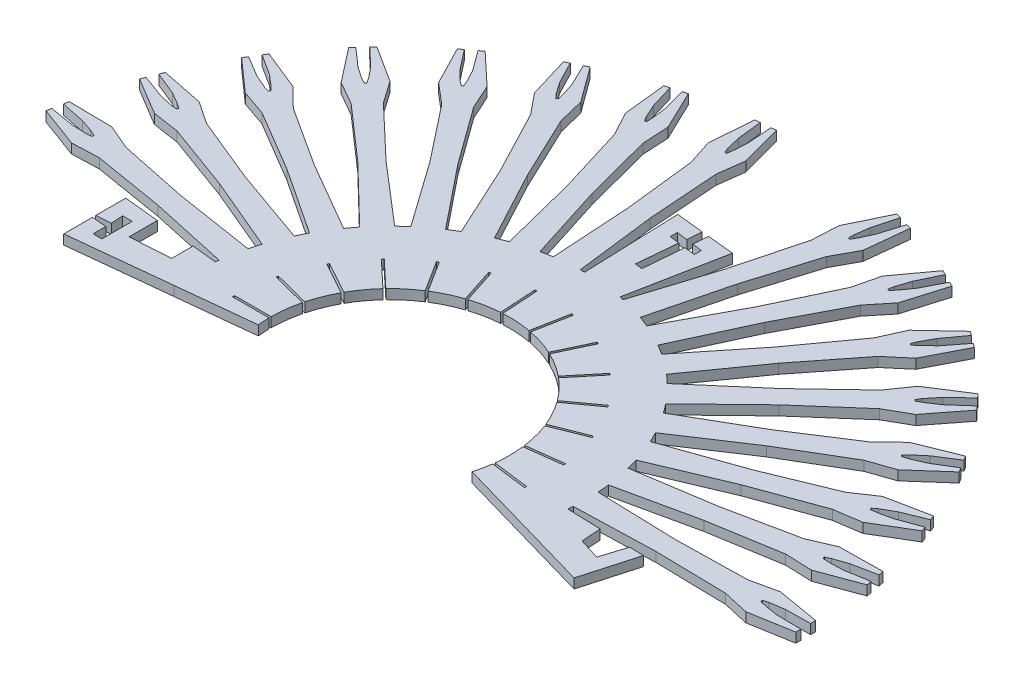
SolidWorks part; units mm, degrees
ref_plane "Front Plane" through (0, 0, 0) normal (0, 0, 1) x (1, 0, 0)
ref_plane "Top Plane" through (0, 0, 0) normal (0, 1, 0) x (1, 0, 0)
ref_plane "Right Plane" through (0, 0, 0) normal (1, 0, 0) x (0, 0, -1)
sketch "Sketch1" plane through (0, 0, 0) normal (0, 1, 0) x (1, 0, 0)
  line L5558 (72.849, 49.9) -> (72.743, 47.748) construction
  line L5559 (72.743, 47.748) -> (72.425, 45.667) construction
  line L5560 (72.425, 45.667) -> (71.896, 43.656) construction
  line L5561 (71.896, 43.656) -> (71.208, 41.716) construction
  line L5562 (71.208, 41.716) -> (70.309, 39.899) construction
  line L5563 (70.309, 39.899) -> (69.286, 38.171) construction
  line L5564 (69.286, 38.171) -> (66.71, 35.048) construction
  line L5565 (66.71, 35.048) -> (63.588, 32.491) construction
  line L5566 (63.588, 32.491) -> (61.877, 31.45) construction
  line L5567 (61.877, 31.45) -> (60.043, 30.551) construction
  line L5568 (60.043, 30.551) -> (58.12, 29.863) construction
  line L5569 (58.12, 29.863) -> (56.109, 29.333) construction
  line L5570 (56.109, 29.333) -> (54.01, 29.016) construction
  line L5571 (54.01, 29.016) -> (51.876, 28.91) construction
  line L5572 (51.876, 28.91) -> (49.724, 29.016) construction
  line L5573 (49.724, 29.016) -> (47.643, 29.333) construction
  line L5574 (47.643, 29.333) -> (45.632, 29.863) construction
  line L5575 (45.632, 29.863) -> (43.692, 30.551) construction
  line L5576 (43.692, 30.551) -> (41.839, 31.45) construction
  line L5577 (41.839, 31.45) -> (40.128, 32.491) construction
  line L5578 (40.128, 32.491) -> (37.006, 35.048) construction
  line L5579 (37.006, 35.048) -> (34.431, 38.171) construction
  line L5580 (34.431, 38.171) -> (33.408, 39.899) construction
  line L5581 (33.408, 39.899) -> (32.508, 41.716) construction
  line L5582 (32.508, 41.716) -> (31.821, 43.656) construction
  line L5583 (31.821, 43.656) -> (31.291, 45.667) construction
  line L5584 (31.291, 45.667) -> (30.974, 47.748) construction
  line L5585 (30.974, 47.748) -> (30.868, 49.9) construction
  line L5586 (30.868, 49.9) -> (30.974, 52.035) construction
  line L5587 (30.974, 52.035) -> (31.291, 54.134) construction
  line L5588 (31.291, 54.134) -> (31.821, 56.145) construction
  line L5589 (31.821, 56.145) -> (32.508, 58.067) construction
  line L5590 (32.508, 58.067) -> (33.408, 59.919) construction
  line L5591 (33.408, 59.919) -> (34.431, 61.648) construction
  line L5592 (34.431, 61.648) -> (37.006, 64.77) construction
  line L5593 (37.006, 64.77) -> (40.128, 67.328) construction
  line L5594 (40.128, 67.328) -> (41.839, 68.368) construction
  line L5595 (41.839, 68.368) -> (43.692, 69.268) construction
  line L5596 (43.692, 69.268) -> (45.632, 69.956) construction
  line L5597 (45.632, 69.956) -> (47.643, 70.485) construction
  line L5598 (47.643, 70.485) -> (49.724, 70.803) construction
  line L5599 (49.724, 70.803) -> (51.876, 70.908) construction
  line L5600 (51.876, 70.908) -> (54.01, 70.803) construction
  line L5601 (54.01, 70.803) -> (56.109, 70.485) construction
  line L5602 (56.109, 70.485) -> (58.12, 69.956) construction
  line L5603 (58.12, 69.956) -> (60.043, 69.268) construction
  line L5604 (60.043, 69.268) -> (61.877, 68.368) construction
  line L5605 (61.877, 68.368) -> (63.588, 67.328) construction
  line L5606 (63.588, 67.328) -> (66.71, 64.77) construction
  line L5607 (66.71, 64.77) -> (69.286, 61.648) construction
  line L5608 (69.286, 61.648) -> (70.309, 59.919) construction
  line L5609 (70.309, 59.919) -> (71.208, 58.067) construction
  line L5610 (71.208, 58.067) -> (71.896, 56.145) construction
  line L5611 (71.896, 56.145) -> (72.425, 54.134) construction
  line L5612 (72.425, 54.134) -> (72.743, 52.035) construction
  line L5613 (72.743, 52.035) -> (72.849, 49.9) construction
  line L5614 (62.054, 49.9) -> (61.842, 47.854) construction
  line L5615 (61.842, 47.854) -> (61.26, 45.932) construction
  line L5616 (61.26, 45.932) -> (60.307, 44.203) construction
  line L5617 (60.307, 44.203) -> (59.055, 42.704) construction
  line L5618 (59.055, 42.704) -> (57.556, 41.451) construction
  line L5619 (57.556, 41.451) -> (55.827, 40.499) construction
  line L5620 (55.827, 40.499) -> (53.922, 39.917) construction
  line L5621 (53.922, 39.917) -> (51.858, 39.705) construction
  line L5622 (51.858, 39.705) -> (49.795, 39.917) construction
  line L5623 (49.795, 39.917) -> (47.89, 40.499) construction
  line L5624 (47.89, 40.499) -> (46.143, 41.451) construction
  line L5625 (46.143, 41.451) -> (44.644, 42.704) construction
  line L5626 (44.644, 42.704) -> (43.392, 44.203) construction
  line L5627 (43.392, 44.203) -> (42.439, 45.932) construction
  line L5628 (42.439, 45.932) -> (41.857, 47.854) construction
  line L5629 (41.857, 47.854) -> (41.645, 49.9) construction
  line L5630 (41.645, 49.9) -> (41.857, 51.964) construction
  line L5631 (41.857, 51.964) -> (42.439, 53.869) construction
  line L5632 (42.439, 53.869) -> (43.392, 55.615) construction
  line L5633 (43.392, 55.615) -> (44.644, 57.115) construction
  line L5634 (44.644, 57.115) -> (46.143, 58.367) construction
  line L5635 (46.143, 58.367) -> (47.89, 59.32) construction
  line L5636 (47.89, 59.32) -> (49.795, 59.902) construction
  line L5637 (49.795, 59.902) -> (51.858, 60.113) construction
  line L5638 (51.858, 60.113) -> (53.922, 59.902) construction
  line L5639 (53.922, 59.902) -> (55.827, 59.32) construction
  line L5640 (55.827, 59.32) -> (57.556, 58.367) construction
  line L5641 (57.556, 58.367) -> (59.055, 57.115) construction
  line L5642 (59.055, 57.115) -> (60.307, 55.615) construction
  line L5643 (60.307, 55.615) -> (61.26, 53.869) construction
  line L5644 (61.26, 53.869) -> (61.842, 51.964) construction
  line L5645 (61.842, 51.964) -> (62.054, 49.9) construction
  line L5646 (30.85, 49.9) -> (51.841, 49.9) construction
  line L5647 (53.675, 70.82) -> (51.841, 49.9) construction
  line L5648 (72.531, 46.249) -> (51.858, 49.9) construction
  line L5649 (72.796, 48.436) -> (51.841, 49.9) construction
  line L5650 (51.488, 70.891) -> (51.841, 49.9) construction
  line L5651 (55.862, 70.52) -> (51.858, 49.9) construction
  line L5652 (30.956, 47.696) -> (51.841, 49.9) construction
  line L5653 (30.956, 52.088) -> (51.841, 49.9) construction
  line L5654 (72.037, 44.115) -> (51.841, 49.9) construction
  line L5655 (62.406, 49.177) -> (67.045, 49.424) construction
  line L5656 (67.345, 50.077) -> (67.469, 50.324) construction
  line L5657 (67.469, 50.324) -> (67.68, 50.377) construction
  line L5658 (67.68, 50.377) -> (67.892, 50.271) construction
  line L5659 (67.892, 50.271) -> (67.945, 50.059) construction
  line L5660 (67.945, 50.059) -> (67.839, 49.848) construction
  line L5661 (67.839, 49.848) -> (67.628, 49.759) construction
  line L5662 (67.628, 49.759) -> (67.416, 49.865) construction
  line L5663 (67.416, 49.865) -> (67.345, 50.077) construction
  line L5664 (69.832, 50.094) -> (69.938, 50.341) construction
  line L5665 (69.938, 50.341) -> (70.168, 50.394) construction
  line L5666 (70.168, 50.394) -> (70.379, 50.288) construction
  line L5667 (70.379, 50.288) -> (70.432, 50.077) construction
  line L5668 (70.432, 50.077) -> (70.326, 49.865) construction
  line L5669 (70.326, 49.865) -> (70.115, 49.777) construction
  line L5670 (70.115, 49.777) -> (69.903, 49.883) construction
  line L5671 (69.903, 49.883) -> (69.832, 50.094) construction
  line L5672 (67.045, 49.424) -> (71.702, 49.477) construction
  line L5673 (71.914, 50.094) -> (71.702, 49.477) construction
  line L5674 (62.389, 50.835) -> (67.045, 50.659) construction
  line L5675 (67.045, 50.659) -> (71.702, 50.712) construction
  line L5676 (71.914, 50.094) -> (71.702, 50.712) construction
  line L5677 (70.132, 50.377) -> (67.645, 50.359) construction
  line L5678 (70.15, 49.777) -> (67.645, 49.742) construction
  line L5679 (57.344, 49.953) -> (51.841, 49.9) construction
  line L5680 (62.353, 51.118) -> (66.887, 52.229) construction
  line L5681 (67.045, 52.917) -> (67.345, 53.252) construction
  line L5682 (67.345, 53.252) -> (67.557, 53.199) construction
  line L5683 (67.557, 53.199) -> (67.663, 52.987) construction
  line L5684 (67.663, 52.987) -> (67.61, 52.776) construction
  line L5685 (67.61, 52.776) -> (67.398, 52.652) construction
  line L5686 (67.398, 52.652) -> (67.187, 52.723) construction
  line L5687 (67.187, 52.723) -> (67.045, 52.917) construction
  line L5688 (69.48, 53.393) -> (69.779, 53.746) construction
  line L5689 (69.779, 53.746) -> (69.991, 53.693) construction
  line L5690 (69.991, 53.693) -> (70.097, 53.481) construction
  line L5691 (70.097, 53.481) -> (70.044, 53.269) construction
  line L5692 (70.044, 53.269) -> (69.832, 53.128) construction
  line L5693 (69.832, 53.128) -> (69.621, 53.217) construction
  line L5694 (69.621, 53.217) -> (69.48, 53.393) construction
  line L5695 (66.887, 52.229) -> (71.455, 53.128) construction
  line L5696 (71.543, 53.763) -> (71.455, 53.128) construction
  line L5697 (62.036, 52.758) -> (66.64, 53.428) construction
  line L5698 (66.64, 53.428) -> (71.208, 54.328) construction
  line L5699 (71.543, 53.781) -> (71.208, 54.328) construction
  line L5700 (69.744, 53.728) -> (67.292, 53.252) construction
  line L5701 (69.85, 53.128) -> (67.416, 52.634) construction
  line L5702 (57.238, 50.959) -> (51.841, 49.9) construction
  line L5703 (61.965, 53.023) -> (66.199, 54.945) construction
  line L5704 (66.234, 55.651) -> (66.446, 56.039) construction
  line L5705 (66.446, 56.039) -> (66.693, 56.021) construction
  line L5706 (66.693, 56.021) -> (66.851, 55.827) construction
  line L5707 (66.851, 55.827) -> (66.64, 55.457) construction
  line L5708 (66.64, 55.457) -> (66.393, 55.492) construction
  line L5709 (66.393, 55.492) -> (66.234, 55.651) construction
  line L5710 (68.545, 56.568) -> (68.756, 56.956) construction
  line L5711 (68.756, 56.956) -> (69.003, 56.938) construction
  line L5712 (69.003, 56.938) -> (69.162, 56.744) construction
  line L5713 (69.162, 56.744) -> (68.95, 56.374) construction
  line L5714 (68.95, 56.374) -> (68.703, 56.409) construction
  line L5715 (68.703, 56.409) -> (68.545, 56.568) construction
  line L5716 (66.199, 54.945) -> (70.52, 56.656) construction
  line L5717 (70.503, 57.309) -> (70.52, 56.656) construction
  line L5718 (61.348, 54.575) -> (65.74, 56.092) construction
  line L5719 (65.74, 56.092) -> (70.079, 57.803) construction
  line L5720 (70.503, 57.309) -> (70.079, 57.803) construction
  line L5721 (68.739, 56.938) -> (66.41, 56.021) construction
  line L5722 (68.968, 56.374) -> (66.64, 55.439) construction
  line L5723 (56.956, 51.929) -> (51.841, 49.9) construction
  line L5724 (61.225, 54.822) -> (65.035, 57.485) construction
  line L5725 (64.946, 58.191) -> (65.07, 58.614) construction
  line L5726 (65.07, 58.614) -> (65.317, 58.632) construction
  line L5727 (65.317, 58.632) -> (65.493, 58.473) construction
  line L5728 (65.493, 58.473) -> (65.528, 58.244) construction
  line L5729 (65.528, 58.244) -> (65.37, 58.05) construction
  line L5730 (65.37, 58.05) -> (64.946, 58.191) construction
  line L5731 (67.045, 59.514) -> (67.169, 59.937) construction
  line L5732 (67.169, 59.937) -> (67.416, 59.955) construction
  line L5733 (67.416, 59.955) -> (67.592, 59.796) construction
  line L5734 (67.592, 59.796) -> (67.628, 59.567) construction
  line L5735 (67.628, 59.567) -> (67.469, 59.373) construction
  line L5736 (67.469, 59.373) -> (67.045, 59.514) construction
  line L5737 (65.035, 57.485) -> (68.968, 59.972) construction
  line L5738 (68.827, 60.607) -> (68.968, 59.972) construction
  line L5739 (60.325, 56.233) -> (64.382, 58.526) construction
  line L5740 (64.382, 58.526) -> (68.315, 61.013) construction
  line L5741 (68.827, 60.607) -> (68.315, 61.013) construction
  line L5742 (67.169, 59.919) -> (65.052, 58.579) construction
  line L5743 (67.486, 59.39) -> (65.37, 58.067) construction
  line L5744 (56.497, 52.828) -> (51.858, 49.9) construction
  line L5745 (60.149, 56.444) -> (63.429, 59.761) construction
  line L5746 (63.2, 60.448) -> (63.147, 60.678) construction
  line L5747 (63.147, 60.678) -> (63.288, 60.889) construction
  line L5748 (63.288, 60.889) -> (63.5, 60.942) construction
  line L5749 (63.5, 60.942) -> (63.712, 60.837) construction
  line L5750 (63.712, 60.837) -> (63.765, 60.607) construction
  line L5751 (63.765, 60.607) -> (63.659, 60.396) construction
  line L5752 (63.659, 60.396) -> (63.412, 60.343) construction
  line L5753 (63.412, 60.343) -> (63.2, 60.448) construction
  line L5754 (65.017, 62.124) -> (64.964, 62.371) construction
  line L5755 (64.964, 62.371) -> (65.105, 62.583) construction
  line L5756 (65.105, 62.583) -> (65.317, 62.636) construction
  line L5757 (65.317, 62.636) -> (65.528, 62.53) construction
  line L5758 (65.528, 62.53) -> (65.581, 62.283) construction
  line L5759 (65.581, 62.283) -> (65.476, 62.071) construction
  line L5760 (65.476, 62.071) -> (65.229, 62.018) construction
  line L5761 (65.229, 62.018) -> (65.017, 62.124) construction
  line L5762 (63.429, 59.761) -> (66.834, 62.936) construction
  line L5763 (66.587, 63.535) -> (66.834, 62.936) construction
  line L5764 (59.02, 57.679) -> (62.583, 60.678) construction
  line L5765 (62.583, 60.678) -> (66.005, 63.835) construction
  line L5766 (66.587, 63.535) -> (66.005, 63.835) construction
  line L5767 (65.07, 62.548) -> (63.235, 60.854) construction
  line L5768 (65.493, 62.089) -> (63.659, 60.396) construction
  line L5769 (55.88, 53.622) -> (51.841, 49.9) construction
  line L5770 (58.808, 57.873) -> (61.419, 61.718) construction
  line L5771 (61.083, 62.353) -> (60.995, 62.583) construction
  line L5772 (60.995, 62.583) -> (61.083, 62.794) construction
  line L5773 (61.083, 62.794) -> (61.295, 62.9) construction
  line L5774 (61.295, 62.9) -> (61.507, 62.83) construction
  line L5775 (61.507, 62.83) -> (61.613, 62.618) construction
  line L5776 (61.613, 62.618) -> (61.524, 62.371) construction
  line L5777 (61.524, 62.371) -> (61.313, 62.301) construction
  line L5778 (61.313, 62.301) -> (61.083, 62.353) construction
  line L5779 (62.565, 64.329) -> (62.477, 64.576) construction
  line L5780 (62.477, 64.576) -> (62.565, 64.788) construction
  line L5781 (62.565, 64.788) -> (62.777, 64.893) construction
  line L5782 (62.777, 64.893) -> (62.988, 64.805) construction
  line L5783 (62.988, 64.805) -> (63.094, 64.594) construction
  line L5784 (63.094, 64.594) -> (63.006, 64.364) construction
  line L5785 (63.006, 64.364) -> (62.794, 64.276) construction
  line L5786 (62.794, 64.276) -> (62.565, 64.329) construction
  line L5787 (61.419, 61.718) -> (64.206, 65.458) construction
  line L5788 (63.835, 66.005) -> (64.206, 65.458) construction
  line L5789 (57.485, 58.861) -> (60.431, 62.459) construction
  line L5790 (60.431, 62.459) -> (63.2, 66.199) construction
  line L5791 (63.835, 66.005) -> (63.2, 66.199) construction
  line L5792 (62.53, 64.752) -> (61.031, 62.759) construction
  line L5793 (63.024, 64.382) -> (61.524, 62.389) construction
  line L5794 (55.122, 54.31) -> (51.858, 49.9) construction
  line L5795 (57.238, 59.002) -> (59.09, 63.271) construction
  line L5796 (58.649, 63.835) -> (58.508, 64.047) construction
  line L5797 (58.508, 64.047) -> (58.561, 64.258) construction
  line L5798 (58.561, 64.258) -> (58.755, 64.417) construction
  line L5799 (58.755, 64.417) -> (58.967, 64.364) construction
  line L5800 (58.967, 64.364) -> (59.126, 64.17) construction
  line L5801 (59.126, 64.17) -> (59.073, 63.941) construction
  line L5802 (59.073, 63.941) -> (58.879, 63.8) construction
  line L5803 (58.879, 63.8) -> (58.649, 63.835) construction
  line L5804 (59.743, 66.058) -> (59.602, 66.269) construction
  line L5805 (59.602, 66.269) -> (59.655, 66.481) construction
  line L5806 (59.655, 66.481) -> (59.849, 66.604) construction
  line L5807 (59.849, 66.604) -> (60.06, 66.587) construction
  line L5808 (60.06, 66.587) -> (60.219, 66.393) construction
  line L5809 (60.219, 66.393) -> (60.166, 66.163) construction
  line L5810 (60.166, 66.163) -> (59.972, 66.022) construction
  line L5811 (59.972, 66.022) -> (59.743, 66.058) construction
  line L5812 (59.09, 63.271) -> (61.136, 67.451) construction
  line L5813 (60.695, 67.927) -> (61.136, 67.451) construction
  line L5814 (55.739, 59.743) -> (57.979, 63.818) construction
  line L5815 (57.979, 63.818) -> (60.025, 67.998) construction
  line L5816 (60.678, 67.927) -> (60.025, 67.998) construction
  line L5817 (59.619, 66.463) -> (58.526, 64.223) construction
  line L5818 (60.184, 66.181) -> (59.073, 63.941) construction
  line L5819 (54.257, 54.822) -> (51.841, 49.9) construction
  line L5820 (55.457, 59.849) -> (56.497, 64.382) construction
  line L5821 (55.951, 64.841) -> (55.792, 64.999) construction
  line L5822 (55.792, 64.999) -> (55.792, 65.246) construction
  line L5823 (55.792, 65.246) -> (55.951, 65.423) construction
  line L5824 (55.951, 65.423) -> (56.18, 65.423) construction
  line L5825 (56.18, 65.423) -> (56.339, 65.264) construction
  line L5826 (56.339, 65.264) -> (56.339, 65.035) construction
  line L5827 (56.339, 65.035) -> (56.18, 64.876) construction
  line L5828 (56.18, 64.876) -> (55.951, 64.841) construction
  line L5829 (56.603, 67.239) -> (56.444, 67.398) construction
  line L5830 (56.444, 67.398) -> (56.444, 67.628) construction
  line L5831 (56.444, 67.628) -> (56.603, 67.822) construction
  line L5832 (56.603, 67.822) -> (56.85, 67.822) construction
  line L5833 (56.85, 67.822) -> (57.009, 67.663) construction
  line L5834 (57.009, 67.663) -> (57.009, 67.416) construction
  line L5835 (57.009, 67.416) -> (56.85, 67.257) construction
  line L5836 (56.85, 67.257) -> (56.603, 67.239) construction
  line L5837 (56.497, 64.382) -> (57.732, 68.88) construction
  line L5838 (57.203, 69.25) -> (57.732, 68.88) construction
  line L5839 (53.852, 60.29) -> (55.298, 64.717) construction
  line L5840 (55.298, 64.717) -> (56.533, 69.197) construction
  line L5841 (57.185, 69.25) -> (56.533, 69.197) construction
  line L5842 (56.427, 67.61) -> (55.757, 65.211) construction
  line L5843 (57.009, 67.451) -> (56.356, 65.035) construction
  line L5844 (53.305, 55.192) -> (51.841, 49.9) construction
  line L5845 (51.664, 60.484) -> (50.994, 65.088) construction
  line L5846 (50.324, 65.317) -> (50.112, 65.423) construction
  line L5847 (50.112, 65.423) -> (50.024, 65.634) construction
  line L5848 (50.024, 65.634) -> (50.112, 65.846) construction
  line L5849 (50.112, 65.846) -> (50.324, 65.952) construction
  line L5850 (50.324, 65.952) -> (50.553, 65.846) construction
  line L5851 (50.553, 65.846) -> (50.641, 65.634) construction
  line L5852 (50.641, 65.634) -> (50.553, 65.423) construction
  line L5853 (50.553, 65.423) -> (50.324, 65.317) construction
  line L5854 (50.077, 67.786) -> (49.865, 67.892) construction
  line L5855 (49.865, 67.892) -> (49.795, 68.104) construction
  line L5856 (49.795, 68.104) -> (49.865, 68.315) construction
  line L5857 (49.865, 68.315) -> (50.077, 68.421) construction
  line L5858 (50.077, 68.421) -> (50.324, 68.315) construction
  line L5859 (50.324, 68.315) -> (50.394, 68.104) construction
  line L5860 (50.394, 68.104) -> (50.324, 67.892) construction
  line L5861 (50.324, 67.892) -> (50.077, 67.786) construction
  line L5862 (50.994, 65.088) -> (50.535, 69.727) construction
  line L5863 (49.918, 69.885) -> (50.535, 69.727) construction
  line L5864 (50.006, 60.325) -> (49.759, 64.964) construction
  line L5865 (49.759, 64.964) -> (49.318, 69.603) construction
  line L5866 (49.9, 69.885) -> (49.318, 69.603) construction
  line L5867 (49.777, 68.068) -> (50.024, 65.599) construction
  line L5868 (50.377, 68.139) -> (50.624, 65.652) construction
  line L5869 (51.312, 55.368) -> (51.858, 49.9) construction
  line L5870 (49.724, 60.272) -> (48.225, 64.664) construction
  line L5871 (47.519, 64.788) -> (47.308, 64.841) construction
  line L5872 (47.308, 64.841) -> (47.184, 65.052) construction
  line L5873 (47.184, 65.052) -> (47.237, 65.264) construction
  line L5874 (47.237, 65.264) -> (47.413, 65.387) construction
  line L5875 (47.413, 65.387) -> (47.66, 65.334) construction
  line L5876 (47.66, 65.334) -> (47.784, 65.158) construction
  line L5877 (47.784, 65.158) -> (47.731, 64.946) construction
  line L5878 (47.731, 64.946) -> (47.519, 64.788) construction
  line L5879 (46.831, 67.169) -> (46.62, 67.222) construction
  line L5880 (46.62, 67.222) -> (46.496, 67.433) construction
  line L5881 (46.496, 67.433) -> (46.549, 67.645) construction
  line L5882 (46.549, 67.645) -> (46.725, 67.769) construction
  line L5883 (46.725, 67.769) -> (46.972, 67.716) construction
  line L5884 (46.972, 67.716) -> (47.096, 67.539) construction
  line L5885 (47.096, 67.539) -> (47.043, 67.328) construction
  line L5886 (47.043, 67.328) -> (46.831, 67.169) construction
  line L5887 (48.225, 64.664) -> (46.937, 69.144) construction
  line L5888 (46.284, 69.18) -> (46.937, 69.144) construction
  line L5889 (48.119, 59.796) -> (47.043, 64.329) construction
  line L5890 (47.043, 64.329) -> (45.738, 68.809) construction
  line L5891 (46.267, 69.18) -> (45.738, 68.792) construction
  line L5892 (46.478, 67.381) -> (47.166, 64.982) construction
  line L5893 (47.061, 67.557) -> (47.766, 65.158) construction
  line L5894 (50.324, 55.174) -> (51.841, 49.9) construction
  line L5895 (47.854, 59.708) -> (45.579, 63.747) construction
  line L5896 (44.873, 63.729) -> (44.662, 63.765) construction
  line L5897 (44.662, 63.765) -> (44.503, 63.923) construction
  line L5898 (44.503, 63.923) -> (44.503, 64.153) construction
  line L5899 (44.503, 64.153) -> (44.662, 64.311) construction
  line L5900 (44.662, 64.311) -> (44.891, 64.311) construction
  line L5901 (44.891, 64.311) -> (45.05, 64.135) construction
  line L5902 (45.05, 64.135) -> (45.05, 63.923) construction
  line L5903 (45.05, 63.923) -> (44.873, 63.729) construction
  line L5904 (43.762, 65.952) -> (43.55, 65.969) construction
  line L5905 (43.55, 65.969) -> (43.356, 66.128) construction
  line L5906 (43.356, 66.128) -> (43.392, 66.375) construction
  line L5907 (43.392, 66.375) -> (43.55, 66.534) construction
  line L5908 (43.55, 66.534) -> (43.78, 66.534) construction
  line L5909 (43.78, 66.534) -> (43.938, 66.34) construction
  line L5910 (43.938, 66.34) -> (43.938, 66.128) construction
  line L5911 (43.938, 66.128) -> (43.762, 65.952) construction
  line L5912 (45.579, 63.747) -> (43.498, 67.91) construction
  line L5913 (42.845, 67.839) -> (43.498, 67.91) construction
  line L5914 (46.373, 58.949) -> (44.485, 63.2) construction
  line L5915 (44.485, 63.2) -> (42.386, 67.363) construction
  line L5916 (42.827, 67.839) -> (42.386, 67.363) construction
  line L5917 (43.374, 66.111) -> (44.485, 63.87) construction
  line L5918 (43.921, 66.393) -> (45.032, 64.153) construction
  line L5919 (49.389, 54.804) -> (51.841, 49.9) construction
  line L5920 (46.126, 58.808) -> (43.145, 62.371) construction
  line L5921 (42.457, 62.23) -> (42.245, 62.195) construction
  line L5922 (42.245, 62.195) -> (42.051, 62.336) construction
  line L5923 (42.051, 62.336) -> (41.998, 62.565) construction
  line L5924 (41.998, 62.565) -> (42.139, 62.759) construction
  line L5925 (42.139, 62.759) -> (42.369, 62.777) construction
  line L5926 (42.369, 62.777) -> (42.563, 62.653) construction
  line L5927 (42.563, 62.653) -> (42.58, 62.442) construction
  line L5928 (42.58, 62.442) -> (42.457, 62.23) construction
  line L5929 (40.958, 64.188) -> (40.746, 64.17) construction
  line L5930 (40.746, 64.17) -> (40.552, 64.294) construction
  line L5931 (40.552, 64.294) -> (40.499, 64.541) construction
  line L5932 (40.499, 64.541) -> (40.64, 64.717) construction
  line L5933 (40.64, 64.717) -> (40.869, 64.752) construction
  line L5934 (40.869, 64.752) -> (41.063, 64.611) construction
  line L5935 (41.063, 64.611) -> (41.081, 64.4) construction
  line L5936 (41.081, 64.4) -> (40.958, 64.188) construction
  line L5937 (43.145, 62.371) -> (40.323, 66.075) construction
  line L5938 (39.705, 65.881) -> (40.323, 66.075) construction
  line L5939 (44.803, 57.803) -> (42.157, 61.63) construction
  line L5940 (42.157, 61.63) -> (39.352, 65.334) construction
  line L5941 (39.705, 65.881) -> (39.352, 65.334) construction
  line L5942 (40.534, 64.276) -> (42.051, 62.301) construction
  line L5943 (41.028, 64.647) -> (42.545, 62.671) construction
  line L5944 (48.525, 54.275) -> (51.858, 49.9) construction
  line L5945 (44.591, 57.609) -> (41.01, 60.572) construction
  line L5946 (40.358, 60.29) -> (40.146, 60.219) construction
  line L5947 (40.146, 60.219) -> (39.934, 60.325) construction
  line L5948 (39.934, 60.325) -> (39.846, 60.537) construction
  line L5949 (39.846, 60.537) -> (39.952, 60.748) construction
  line L5950 (39.952, 60.748) -> (40.164, 60.819) construction
  line L5951 (40.164, 60.819) -> (40.375, 60.748) construction
  line L5952 (40.375, 60.748) -> (40.464, 60.537) construction
  line L5953 (40.464, 60.537) -> (40.358, 60.29) construction
  line L5954 (38.523, 61.965) -> (38.312, 61.877) construction
  line L5955 (38.312, 61.877) -> (38.1, 61.983) construction
  line L5956 (38.1, 61.983) -> (38.012, 62.195) construction
  line L5957 (38.012, 62.195) -> (38.118, 62.406) construction
  line L5958 (38.118, 62.406) -> (38.329, 62.495) construction
  line L5959 (38.329, 62.495) -> (38.541, 62.406) construction
  line L5960 (38.541, 62.406) -> (38.629, 62.195) construction
  line L5961 (38.629, 62.195) -> (38.523, 61.965) construction
  line L5962 (41.01, 60.572) -> (37.553, 63.694) construction
  line L5963 (36.989, 63.394) -> (37.553, 63.694) construction
  line L5964 (43.48, 56.374) -> (40.181, 59.655) construction
  line L5965 (40.181, 59.655) -> (36.724, 62.777) construction
  line L5966 (36.971, 63.377) -> (36.724, 62.777) construction
  line L5967 (38.1, 61.965) -> (39.952, 60.29) construction
  line L5968 (38.506, 62.424) -> (40.358, 60.748) construction
  line L5969 (47.784, 53.587) -> (51.841, 49.9) construction
  line L5970 (43.303, 56.145) -> (39.247, 58.402) construction
  line L5971 (38.647, 58.014) -> (38.453, 57.908) construction
  line L5972 (38.453, 57.908) -> (38.223, 57.961) construction
  line L5973 (38.223, 57.961) -> (38.118, 58.173) construction
  line L5974 (38.118, 58.173) -> (38.171, 58.385) construction
  line L5975 (38.171, 58.385) -> (38.594, 58.455) construction
  line L5976 (38.594, 58.455) -> (38.7, 58.244) construction
  line L5977 (38.7, 58.244) -> (38.647, 58.014) construction
  line L5978 (36.53, 59.32) -> (36.354, 59.214) construction
  line L5979 (36.354, 59.214) -> (36.107, 59.267) construction
  line L5980 (36.107, 59.267) -> (36.001, 59.478) construction
  line L5981 (36.001, 59.478) -> (36.054, 59.69) construction
  line L5982 (36.054, 59.69) -> (36.477, 59.761) construction
  line L5983 (36.477, 59.761) -> (36.583, 59.549) construction
  line L5984 (36.583, 59.549) -> (36.53, 59.32) construction
  line L5985 (39.247, 58.402) -> (35.278, 60.854) construction
  line L5986 (34.766, 60.448) -> (35.278, 60.837) construction
  line L5987 (42.439, 54.733) -> (38.594, 57.344) construction
  line L5988 (38.594, 57.344) -> (34.625, 59.796) construction
  line L5989 (34.766, 60.431) -> (34.625, 59.796) construction
  line L5990 (36.124, 59.249) -> (38.241, 57.926) construction
  line L5991 (36.442, 59.761) -> (38.559, 58.455) construction
  line L5992 (47.184, 52.776) -> (51.841, 49.9) construction
  line L5993 (42.316, 54.469) -> (37.888, 55.951) construction
  line L5994 (37.377, 55.457) -> (37.218, 55.316) construction
  line L5995 (37.218, 55.316) -> (36.989, 55.316) construction
  line L5996 (36.989, 55.316) -> (36.83, 55.51) construction
  line L5997 (36.83, 55.51) -> (36.848, 55.739) construction
  line L5998 (36.848, 55.739) -> (37.006, 55.898) construction
  line L5999 (37.006, 55.898) -> (37.253, 55.88) construction
  line L6000 (37.253, 55.88) -> (37.412, 55.686) construction
  line L6001 (37.412, 55.686) -> (37.377, 55.457) construction
  line L6002 (35.066, 56.356) -> (34.907, 56.215) construction
  line L6003 (34.907, 56.215) -> (34.678, 56.215) construction
  line L6004 (34.678, 56.215) -> (34.519, 56.409) construction
  line L6005 (34.519, 56.409) -> (34.537, 56.638) construction
  line L6006 (34.537, 56.638) -> (34.696, 56.797) construction
  line L6007 (34.696, 56.797) -> (34.943, 56.78) construction
  line L6008 (34.943, 56.78) -> (35.101, 56.586) construction
  line L6009 (35.101, 56.586) -> (35.066, 56.356) construction
  line L6010 (37.888, 55.951) -> (33.549, 57.626) construction
  line L6011 (33.126, 57.132) -> (33.549, 57.626) construction
  line L6012 (41.716, 52.917) -> (37.447, 54.804) construction
  line L6013 (37.447, 54.804) -> (33.108, 56.48) construction
  line L6014 (33.126, 57.132) -> (33.108, 56.48) construction
  line L6015 (34.678, 56.198) -> (37.006, 55.298) construction
  line L6016 (34.89, 56.78) -> (37.218, 55.88) construction
  line L6017 (46.725, 51.876) -> (51.858, 49.9) construction
  line L6018 (41.628, 52.652) -> (37.024, 53.287) construction
  line L6019 (36.601, 52.705) -> (36.477, 52.529) construction
  line L6020 (36.477, 52.529) -> (36.23, 52.493) construction
  line L6021 (36.23, 52.493) -> (36.054, 52.652) construction
  line L6022 (36.054, 52.652) -> (36.019, 52.899) construction
  line L6023 (36.019, 52.899) -> (36.389, 53.111) construction
  line L6024 (36.389, 53.111) -> (36.583, 52.952) construction
  line L6025 (36.583, 52.952) -> (36.601, 52.705) construction
  line L6026 (34.167, 53.164) -> (34.043, 52.987) construction
  line L6027 (34.043, 52.987) -> (33.796, 52.952) construction
  line L6028 (33.796, 52.952) -> (33.62, 53.111) construction
  line L6029 (33.62, 53.111) -> (33.584, 53.358) construction
  line L6030 (33.584, 53.358) -> (33.955, 53.569) construction
  line L6031 (33.955, 53.569) -> (34.149, 53.411) construction
  line L6032 (34.149, 53.411) -> (34.167, 53.164) construction
  line L6033 (37.024, 53.287) -> (32.438, 54.134) construction
  line L6034 (32.12, 53.587) -> (32.438, 54.134) construction
  line L6035 (41.328, 51.012) -> (36.795, 52.07) construction
  line L6036 (36.795, 52.07) -> (32.226, 52.934) construction
  line L6037 (32.12, 53.569) -> (32.226, 52.934) construction
  line L6038 (33.814, 52.952) -> (36.266, 52.493) construction
  line L6039 (33.92, 53.552) -> (36.371, 53.093) construction
  line L6040 (46.461, 50.906) -> (51.858, 49.9) construction
  line L6041 (57.856, 49.9) -> (57.714, 48.683) construction
  line L6042 (57.714, 48.683) -> (57.379, 47.572) construction
  line L6043 (57.379, 47.572) -> (56.815, 46.567) construction
  line L6044 (56.815, 46.567) -> (56.109, 45.667) construction
  line L6045 (56.109, 45.667) -> (55.21, 44.944) construction
  line L6046 (55.21, 44.944) -> (54.204, 44.397) construction
  line L6047 (54.204, 44.397) -> (53.093, 44.044) construction
  line L6048 (53.093, 44.044) -> (51.876, 43.921) construction
  line L6049 (51.876, 43.921) -> (50.659, 44.044) construction
  line L6050 (50.659, 44.044) -> (49.512, 44.397) construction
  line L6051 (49.512, 44.397) -> (48.507, 44.944) construction
  line L6052 (48.507, 44.944) -> (47.607, 45.667) construction
  line L6053 (47.607, 45.667) -> (46.902, 46.567) construction
  line L6054 (46.902, 46.567) -> (46.337, 47.572) construction
  line L6055 (46.337, 47.572) -> (46.002, 48.683) construction
  line L6056 (46.002, 48.683) -> (45.861, 49.9) construction
  line L6057 (45.861, 49.9) -> (46.002, 51.118) construction
  line L6058 (46.002, 51.118) -> (46.337, 52.246) construction
  line L6059 (46.337, 52.246) -> (46.902, 53.252) construction
  line L6060 (46.902, 53.252) -> (47.607, 54.151) construction
  line L6061 (47.607, 54.151) -> (48.507, 54.875) construction
  line L6062 (48.507, 54.875) -> (49.512, 55.421) construction
  line L6063 (49.512, 55.421) -> (50.659, 55.774) construction
  line L6064 (50.659, 55.774) -> (51.876, 55.898) construction
  line L6065 (51.876, 55.898) -> (53.093, 55.774) construction
  line L6066 (53.093, 55.774) -> (54.204, 55.421) construction
  line L6067 (54.204, 55.421) -> (55.21, 54.875) construction
  line L6068 (55.21, 54.875) -> (56.109, 54.151) construction
  line L6069 (56.109, 54.151) -> (56.815, 53.252) construction
  line L6070 (56.815, 53.252) -> (57.379, 52.246) construction
  line L6071 (57.379, 52.246) -> (57.714, 51.118) construction
  line L6072 (57.714, 51.118) -> (57.856, 49.9) construction
sketch "Sketch2" plane through (0, 0, 0) normal (0, 1, 0) x (1, 0, 0)
  line L0 (41.7366, 50.9583) -> (36.5552, 51.5014)
  line L1 (51.841, 49.9) -> (53.163, 64.9033) construction
  line L2 (30.956, 52.088) -> (51.841, 49.9) construction
  line L3 (36.5552, 51.5014) -> (36.5552, 48.2869)
  line L4 (30.956, 47.696) -> (51.841, 49.9) construction
  line L5 (36.5552, 48.2869) -> (41.7327, 48.8337)
  line L7 (61.6124, 47.1011) -> (66.5007, 45.7008)
  line L8 (72.037, 44.115) -> (51.841, 49.9) construction
  line L9 (66.5007, 45.7008) -> (67.012, 48.8401)
  line L10 (72.796, 48.436) -> (51.841, 49.9) construction
  line L11 (67.012, 48.8401) -> (61.9609, 49.0012)
  line L12 (62.054, 49.9) -> (61.842, 47.854) construction
  line L13 (51.765, 60.0594) -> (51.586, 65.0642)
  line L14 (51.488, 70.891) -> (51.841, 49.9) construction
  line L15 (51.586, 65.0642) -> (54.7401, 64.7424)
  line L16 (55.862, 70.52) -> (51.858, 49.9) construction
  line L17 (54.7401, 64.7424) -> (53.794, 59.8702)
  circle A0 centre (51.841, 49.9) radius 6.2002
  arc A1 (61.9609, 49.0012) -> (53.794, 59.8702) centre (51.841, 49.9) ccw
  arc A2 (41.7375, 50.967) -> (41.7366, 50.9583) centre (51.841, 49.9) ccw
  arc A3 (41.7327, 48.8337) -> (41.7338, 48.8238) centre (51.841, 49.9) ccw
  arc A4 (41.7338, 48.8238) -> (61.6124, 47.1011) centre (51.841, 49.9) ccw
  arc A5 (51.765, 60.0594) -> (41.7375, 50.967) centre (51.841, 49.9) ccw
extrude "Boss-Extrude1" add sketch "Sketch2" along normal blind 0.5
sketch "Sketch3" plane through (0, 0, 0) normal (0, 1, 0) x (1, 0, 0)
  line L0 (34.0857, 50.3207) -> (32.7162, 50.6322) construction
  line L1 (30.85, 49.9) -> (51.841, 49.9) construction
  line L2 (41.7282, 50.4911) -> (37.2554, 50.2819) construction
  line L3 (32.7162, 50.6322) -> (32.323, 50.6098) construction
  line L4 (32.323, 50.6098) -> (30.1914, 50.3756) construction
  line L5 (30.1914, 50.3756) -> (30.1967, 50.3818) construction
  line L7 (37.2554, 50.2819) -> (34.0857, 50.3207) construction
  line L8 (30.9964, 50.2252) -> (31.0029, 50.2183) construction
  line L9 (30.8082, 50.2183) -> (31.0029, 50.2183) construction
  line L11 (41.7282, 50.4911) -> (41.7282, 49.4512) construction
  line L12 (31.194, 49.6753) -> (31.1199, 49.6329) construction
  line L13 (30.8082, 50.2183) -> (30.8031, 50.209) construction
  line L14 (30.8031, 50.209) -> (30.1967, 50.2521) construction
  line L15 (30.7788, 49.6329) -> (31.1199, 49.6329) construction
  line L16 (30.1967, 50.2521) -> (30.1967, 50.3818) construction
  line L17 (30.3951, 49.2413) -> (30.1967, 49.4512) construction
  line L18 (30.8191, 49.1966) -> (30.3951, 49.2413) construction
  line L19 (32.6688, 49.1966) -> (30.8191, 49.1966) construction
  line L20 (41.7282, 49.4512) -> (37.2554, 49.5186) construction
  line L21 (34.213, 49.341) -> (32.6688, 49.1966) construction
  line L22 (30.7788, 49.6329) -> (30.7516, 49.685) construction
  line L23 (30.7516, 49.685) -> (30.1967, 49.6405) construction
  line L24 (30.1967, 49.6405) -> (30.1967, 49.4512) construction
  line L25 (37.2554, 49.5186) -> (34.213, 49.341) construction
  line L26 (51.841, 49.9) -> (28.9127, 49.9) construction
  line L27 (32.2273, 50.0311) -> (31.5743, 50.1336)
  line L28 (30.2995, 50.1535) -> (30.2995, 50.4159)
  line L29 (30.2995, 50.4159) -> (32.5107, 50.796)
  line L30 (32.5107, 50.796) -> (33.8631, 50.4911)
  line L31 (33.8631, 50.4911) -> (37.549, 50.4176)
  line L32 (37.549, 50.4176) -> (41.8575, 50.5468)
  line L33 (41.8575, 50.5468) -> (41.8575, 49.2532)
  line L34 (32.2273, 50.0311) -> (32.5881, 49.9474)
  line L35 (32.5881, 49.9474) -> (32.5881, 49.8526)
  line L36 (31.5743, 50.1336) -> (30.2995, 50.1535)
  line L37 (37.549, 49.3824) -> (41.8575, 49.2532)
  line L38 (33.8631, 49.3089) -> (37.549, 49.3824)
  line L39 (32.5107, 49.004) -> (33.8631, 49.3089)
  line L40 (30.2995, 49.3841) -> (32.5107, 49.004)
  line L41 (31.5743, 49.6664) -> (30.2995, 49.6465)
  line L42 (30.2995, 49.6465) -> (30.2995, 49.3841)
  line L43 (32.323, 49.7782) -> (31.5743, 49.6664)
  line L44 (32.323, 49.7782) -> (32.5881, 49.8526)
  circle A0 centre (32.2123, 49.6) radius 0.1651 construction
  circle A1 centre (30.8082, 50.2183) radius 0.1651 construction
  circle A2 centre (32.2123, 49.9) radius 0.1814 construction
  circle A3 centre (32.2123, 50.1956) radius 0.1651 construction
  circle A4 centre (31.0766, 50.796) radius 0.1651 construction
  arc A5 (31.1468, 50.2004) -> (30.9964, 50.2252) centre (31.1468, 50.6691) cw construction
  circle A6 centre (32.2123, 49.9) radius 0.3 construction
  arc A7 (31.4269, 49.7372) -> (31.194, 49.6753) centre (31.4269, 49.2685) ccw construction
  circle A8 centre (30.0456, 50.6997) radius 0.1651 construction
  point P21 (41.7282, 49.9)
  point P54 (41.7282, 49.9)
  point P60 (41.8575, 49.9)
  point P68 (32.5881, 49.9)
extrude "Boss-Extrude2" add sketch "Sketch3" along normal blind 0.5
sketch "Sketch5" plane through (0, 0, 0) normal (0, 1, 0) x (1, 0, 0)
  line L0 (51.841, 49.9) -> (51.841, 47.986)
  line L1 (30.85, 49.9) -> (51.841, 49.9) construction
  line L2 (51.841, 49.9) -> (47.5187, 49.9)
  line L4 (47.5187, 49.9) -> (51.841, 47.986)
extrude "Boss-Extrude3" add sketch "Sketch5" along normal blind 0.5 separate body
pattern_circular "CirPattern1" count 18 over 180 about axis through (51.841, 0, -49.9) along (0, 1, 0) of "Boss-Extrude2"
sketch "Sketch8" plane through (0, 0, 0) normal (0, 1, 0) x (1, 0, 0)
  line L0 (36.5552, 48.2869) -> (27.9956, 47.1697)
  line L1 (27.9956, 47.1697) -> (27.9956, 52.8907)
  line L2 (27.9956, 52.8907) -> (36.5552, 51.5014)
  line L3 (36.5552, 51.5014) -> (36.5552, 48.754)
  line L5 (36.5552, 48.754) -> (36.5552, 48.2869)
  line L6 (51.6556, 72.5266) -> (51.586, 65.0642)
  line L7 (51.586, 65.0642) -> (54.7401, 64.7424)
  line L8 (54.7401, 64.7424) -> (56.407, 72.5266)
  line L9 (56.407, 72.5266) -> (51.6556, 72.5266)
  line L10 (47.955, 51.5014) -> (46.9983, 48.798)
  line L11 (46.9983, 48.798) -> (52.8392, 46.1614)
  line L12 (52.8392, 46.1614) -> (54.7401, 51.7191)
  line L13 (56.497, 52.828) -> (51.858, 49.9) construction
  line L14 (54.7401, 51.7191) -> (47.955, 51.5014)
extrude "Cut-Extrude4" cut sketch "Sketch8" against normal blind 0.5 and the other way through all
sketch "Sketch9" plane through (0, 0, 0) normal (0, 1, 0) x (1, 0, 0)
  line L0 (36.5552, 48.2869) -> (47.0091, 49.3901)
  line L1 (51.841, 49.9) -> (66.5007, 45.7008)
  line L2 (66.5007, 45.7008) -> (51.841, 34.8579)
  line L3 (51.841, 34.8579) -> (36.5552, 48.2869)
  line L4 (47.0091, 49.3901) -> (47.588, 50.4909)
  line L5 (47.588, 50.4909) -> (51.841, 49.9)
extrude "Cut-Extrude6" cut sketch "Sketch9" against normal blind 0.5 and the other way through all
sketch "Sketch12" plane through (0, 0, 0) normal (0, 1, 0) x (1, 0, 0)
  line L0 (36.5552, 51.5014) -> (38.3774, 51.5014)
  line L1 (38.3774, 51.5014) -> (38.3774, 49.8464)
  line L2 (38.3774, 49.8464) -> (40.4501, 49.9851)
  line L3 (40.4501, 49.9851) -> (40.4501, 51.1692)
  line L4 (40.4501, 51.1692) -> (37.3172, 51.7206)
  line L5 (37.3172, 51.7206) -> (36.5552, 51.5014)
  line L6 (66.0368, 49.0067) -> (65.0952, 45.6712)
  line L7 (53.0825, 66.1281) -> (52.9481, 64.1718)
  line L8 (67.012, 48.8401) -> (61.9609, 49.0012) construction
  line L9 (65.2739, 48.8955) -> (64.8588, 47.5883)
  line L10 (64.8588, 47.5883) -> (63.7611, 47.9369)
  line L11 (63.7611, 47.9369) -> (63.678, 49.0649)
  line L12 (63.678, 49.0649) -> (65.5048, 49.0067)
  line L13 (65.5048, 49.0067) -> (65.2739, 48.8955)
  line L14 (65.0952, 45.6712) -> (66.9581, 45.1452)
  line L15 (35.4312, 49.8586) -> (37.3125, 49.9972)
  line L16 (37.3125, 49.9972) -> (37.2663, 50.6247)
  line L17 (37.2663, 50.6247) -> (37.7661, 50.6247)
  line L18 (37.7661, 50.6247) -> (37.7661, 49.0512)
  line L19 (37.7661, 49.0512) -> (37.3125, 49.0512)
  line L20 (37.3125, 49.0512) -> (37.3125, 49.7158)
  line L21 (37.3125, 49.7158) -> (35.4312, 49.8586)
  line L22 (66.9581, 45.1452) -> (67.4623, 48.8914)
  line L23 (67.4623, 48.8914) -> (66.0368, 49.0067)
  line L24 (52.9481, 64.1718) -> (52.3858, 64.243)
  line L25 (52.3858, 64.243) -> (52.3858, 63.8789)
  line L26 (52.3858, 63.8789) -> (52.896, 63.8143)
  line L27 (53.8144, 63.698) -> (53.8144, 64.0546)
  line L28 (53.8144, 64.0546) -> (53.3003, 64.1253)
  line L29 (53.3003, 64.1253) -> (53.4738, 66.0149)
  line L30 (52.896, 63.8143) -> (52.7084, 61.7546)
  line L31 (53.2624, 63.7552) -> (53.8144, 63.698)
  line L32 (52.7084, 61.7546) -> (53.0877, 61.7007)
  line L33 (53.0877, 61.7007) -> (53.2624, 63.7552)
  line L34 (51.841, 49.9) -> (53.5625, 69.0822) construction
  line L35 (53.4738, 66.0149) -> (53.0825, 66.1281)
  circle A0 centre (0, 0) radius 0.1651 construction
  circle A1 centre (52.4393, 65.7495) radius 0.1651 construction
extrude "Cut-Extrude13" cut sketch "Sketch12" along normal blind 10
sketch "Sketch13" plane through (0, 0, 0) normal (0, 1, 0) x (1, 0, 0)
  line L0 (49.3736, 50.47) -> (43.9869, 51.853)
  line L1 (49.3092, 49.8384) -> (43.7478, 49.8384)
  line L2 (49.3092, 49.8384) -> (49.3092, 49.945)
  line L3 (49.3092, 49.945) -> (43.7478, 49.945)
  line L4 (43.7478, 49.8384) -> (43.7478, 49.945)
  line L5 (49.3736, 50.47) -> (49.4001, 50.5733)
  line L6 (49.4001, 50.5733) -> (44.0134, 51.9563)
  line L7 (43.9869, 51.853) -> (44.0134, 51.9563)
  line L8 (49.593, 51.0657) -> (44.7195, 53.7449)
  line L9 (49.593, 51.0657) -> (49.6444, 51.1591)
  line L10 (49.6444, 51.1591) -> (44.7709, 53.8384)
  line L11 (44.7195, 53.7449) -> (44.7709, 53.8384)
  line L12 (49.9537, 51.5881) -> (45.8996, 55.3952)
  line L13 (49.9537, 51.5881) -> (50.0267, 51.6659)
  line L14 (50.0267, 51.6659) -> (45.9726, 55.4729)
  line L15 (45.8996, 55.3952) -> (45.9726, 55.4729)
  line L16 (50.433, 52.0044) -> (47.453, 56.7001)
  line L17 (50.433, 52.0044) -> (50.523, 52.0616)
  line L18 (50.523, 52.0616) -> (47.5431, 56.7572)
  line L19 (47.453, 56.7001) -> (47.5431, 56.7572)
  line L20 (51.0007, 52.2885) -> (49.2822, 57.5777)
  line L21 (51.0007, 52.2885) -> (51.1022, 52.3214)
  line L22 (51.1022, 52.3214) -> (49.3836, 57.6107)
  line L23 (49.2822, 57.5777) -> (49.3836, 57.6107)
  line L24 (51.6213, 52.4224) -> (51.2721, 57.9729)
  line L25 (51.6213, 52.4224) -> (51.7277, 52.4291)
  line L26 (51.7277, 52.4291) -> (51.3785, 57.9796)
  line L27 (51.2721, 57.9729) -> (51.3785, 57.9796)
  line L28 (52.2557, 52.3978) -> (53.2978, 57.8607)
  line L29 (52.2557, 52.3978) -> (52.3604, 52.3778)
  line L30 (52.3604, 52.3778) -> (53.4025, 57.8407)
  line L31 (53.2978, 57.8607) -> (53.4025, 57.8407)
  line L32 (52.864, 52.2162) -> (55.2319, 57.2483)
  line L33 (52.864, 52.2162) -> (52.9605, 52.1708)
  line L34 (52.9605, 52.1708) -> (55.3284, 57.2029)
  line L35 (55.2319, 57.2483) -> (55.3284, 57.2029)
  line L36 (53.408, 51.889) -> (56.953, 56.1742)
  line L37 (53.408, 51.889) -> (53.4902, 51.8211)
  line L38 (53.4902, 51.8211) -> (57.0352, 56.1062)
  line L39 (56.953, 56.1742) -> (57.0352, 56.1062)
  line L40 (53.8536, 51.4369) -> (58.3529, 54.7058)
  line L41 (53.8536, 51.4369) -> (53.9163, 51.3506)
  line L42 (53.9163, 51.3506) -> (58.4156, 54.6195)
  line L43 (58.3529, 54.7058) -> (58.4156, 54.6195)
  line L44 (54.1728, 50.8881) -> (59.3437, 52.9354)
  line L45 (54.1728, 50.8881) -> (54.212, 50.7889)
  line L46 (54.212, 50.7889) -> (59.3829, 52.8362)
  line L47 (59.3437, 52.9354) -> (59.3829, 52.8362)
  line L48 (54.3454, 50.2771) -> (59.863, 50.9742)
  line L49 (54.3454, 50.2771) -> (54.3588, 50.1713)
  line L50 (54.3588, 50.1713) -> (59.8763, 50.8684)
  line L51 (59.863, 50.9742) -> (59.8763, 50.8684)
  line L52 (54.3607, 49.6425) -> (59.8783, 48.9454)
  line L53 (54.3607, 49.6425) -> (54.3473, 49.5367)
  line L54 (54.3473, 49.5367) -> (59.8649, 48.8396)
  line L55 (59.8783, 48.9454) -> (59.8649, 48.8396)
  line L56 (54.2176, 49.0239) -> (59.3885, 46.9766)
  line L57 (54.2176, 49.0239) -> (54.1784, 48.9248)
  line L58 (54.1784, 48.9248) -> (59.3493, 46.8775)
  line L59 (59.3885, 46.9766) -> (59.3493, 46.8775)
  line L60 (53.9253, 48.4604) -> (58.4246, 45.1915)
  line L61 (53.9253, 48.4604) -> (53.8626, 48.3741)
  line L62 (53.8626, 48.3741) -> (58.3619, 45.1052)
  line L63 (58.4246, 45.1915) -> (58.3619, 45.1052)
  line L64 (53.502, 47.9873) -> (57.0469, 43.7022)
  line L65 (53.502, 47.9873) -> (53.4198, 47.9193)
  line L66 (53.4198, 47.9193) -> (56.9648, 43.6342)
  line L67 (57.0469, 43.7022) -> (56.9648, 43.6342)
  line L68 (52.9743, 47.6343) -> (55.3422, 42.6022)
  line L69 (52.9743, 47.6343) -> (52.8778, 47.5889)
  line L70 (52.8778, 47.5889) -> (55.2457, 42.5568)
  line L71 (55.3422, 42.6022) -> (55.2457, 42.5568)
  line L72 (52.3754, 47.4237) -> (53.4175, 41.9608)
  line L73 (52.3754, 47.4237) -> (52.2706, 47.4037)
  line L74 (52.2706, 47.4037) -> (53.3127, 41.9408)
  line L75 (53.4175, 41.9608) -> (53.3127, 41.9408)
  line L76 (51.743, 47.3686) -> (51.3937, 41.8181)
  line L77 (51.743, 47.3686) -> (51.6365, 47.3753)
  line L78 (51.6365, 47.3753) -> (51.2873, 41.8248)
  line L79 (51.3937, 41.8181) -> (51.2873, 41.8248)
  line L80 (51.1167, 47.4725) -> (49.3981, 42.1833)
  line L81 (51.1167, 47.4725) -> (51.0152, 47.5055)
  line L82 (51.0152, 47.5055) -> (49.2967, 42.2162)
  line L83 (49.3981, 42.1833) -> (49.2967, 42.2162)
  line L84 (50.5359, 47.7289) -> (47.5559, 43.0333)
  line L85 (50.5359, 47.7289) -> (50.4459, 47.7861)
  line L86 (50.4459, 47.7861) -> (47.4659, 43.0904)
  line L87 (47.5559, 43.0333) -> (47.4659, 43.0904)
  line L88 (50.0371, 48.1217) -> (45.983, 44.3146)
  line L89 (50.0371, 48.1217) -> (49.9641, 48.1994)
  line L90 (49.9641, 48.1994) -> (45.91, 44.3924)
  line L91 (45.983, 44.3146) -> (45.91, 44.3924)
  line L92 (49.6517, 48.6262) -> (44.7782, 45.9469)
  line L93 (49.6517, 48.6262) -> (49.6004, 48.7196)
  line L94 (49.6004, 48.7196) -> (44.7268, 46.0404)
  line L95 (44.7782, 45.9469) -> (44.7268, 46.0404)
  line L96 (49.4039, 49.2106) -> (44.0172, 47.8276)
  line L97 (49.4039, 49.2106) -> (49.3774, 49.3139)
  line L98 (49.3774, 49.3139) -> (43.9907, 47.9309)
  line L99 (44.0172, 47.8276) -> (43.9907, 47.9309)
  circle A0 centre (51.8411, 49.8993) radius 2.2911
  dimension "D1" = 25
extrude "Cut-Extrude14" cut sketch "Sketch13" along normal through all
